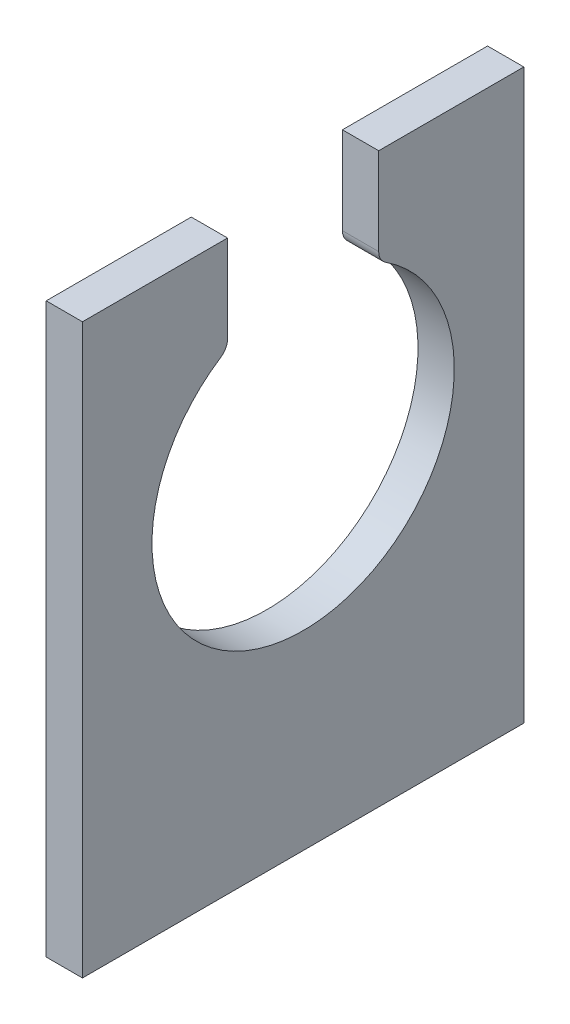
SolidWorks part; units mm, degrees
ref_plane "Front Plane" through (0, 0, 0) normal (0, 0, 1) x (1, 0, 0)
ref_plane "Top Plane" through (0, 0, 0) normal (0, 1, 0) x (1, 0, 0)
ref_plane "Right Plane" through (0, 0, 0) normal (1, 0, 0) x (0, 0, -1)
sketch "Sketch1" plane through (0, 0, 0) normal (1, 0, 0) x (0, 0, -1)
  line L0 (0, 0) -> (0, 94) construction
  line L1 (73, 94) -> (25, 94)
  line L2 (73, 94) -> (73, -94)
  line L3 (73, -94) -> (-73, -94)
  line L4 (-73, 94) -> (-73, -94)
  line L5 (73, 94) -> (-73, -94) construction
  line L6 (73, -94) -> (-73, 94) construction
  line L7 (-25, 94) -> (-25, 65.0977)
  line L8 (25, 94) -> (25, 65.0977)
  line L9 (-25, 94) -> (-73, 94)
  arc A0 (-27.2727, 60.907) -> (27.2727, 60.907) centre (0, 19) ccw
  arc A1 (25, 65.0977) -> (27.2727, 60.907) centre (30, 65.0977) ccw
  arc A2 (-25, 65.0977) -> (-27.2727, 60.907) centre (-30, 65.0977) cw
  point P0 (0, 0)
  point P20 (25, 62.3013)
  point P23 (-25, 62.3013)
  dimension "D3" = 100
  dimension "D6" = 5
  dimension "D1" = 188
  dimension "D2" = 146
  dimension "D4" = 75
  dimension "D5" = 25
extrude "Boss-Extrude1" add sketch "Sketch1" along normal blind 12
